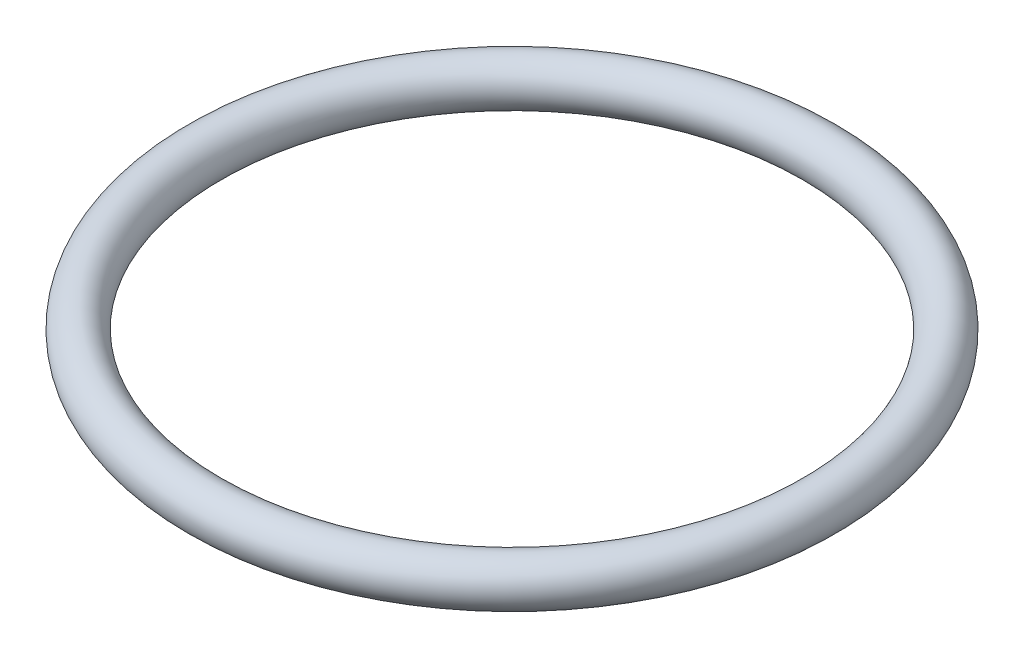
SolidWorks part; units mm, degrees
ref_plane "Front Plane" through (0, 0, 0) normal (0, 0, 1) x (1, 0, 0)
ref_plane "Top Plane" through (0, 0, 0) normal (0, 1, 0) x (1, 0, 0)
ref_plane "Right Plane" through (0, 0, 0) normal (1, 0, 0) x (0, 0, -1)
sketch "Sketch1" plane through (0, 0, 0) normal (0, 0, 1) x (1, 0, 0)
  line L0 (0, 0) -> (0, 3.8108) construction
  circle A0 centre (23.8125, 0) radius 1.7653
  dimension "D1" = 3.5306
  dimension "D2" = 23.8125
revolve "Revolve1" add sketch "Sketch1" angle 360 about L0
